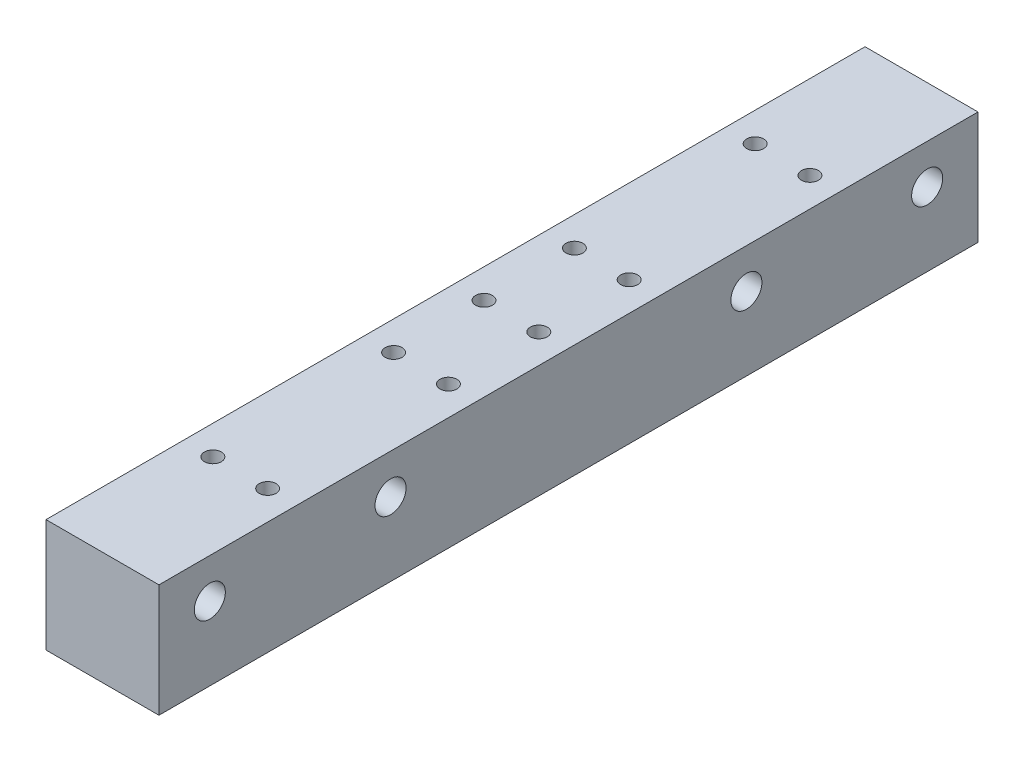
SolidWorks part; units mm, degrees
ref_plane "前视基准面" through (0, 0, 0) normal (0, 0, 1) x (1, 0, 0)
ref_plane "上视基准面" through (0, 0, 0) normal (0, 1, 0) x (1, 0, 0)
ref_plane "右视基准面" through (0, 0, 0) normal (1, 0, 0) x (0, 0, -1)
other "Configuration Table"
sketch "草图1" plane through (0, 0, 0) normal (0, 0, 1) x (1, 0, 0)
  line L1 (-10, -10) -> (10, -10)
  line L2 (-10, -10) -> (-10, 10)
  line L3 (-10, 10) -> (10, 10)
  line L4 (10, -10) -> (10, 10)
  line L5 (-10, -10) -> (10, 10) construction
  line L6 (-10, 10) -> (10, -10) construction
  line L11 (-8, -8) -> (8, 8) construction
  line L12 (-8, 8) -> (8, -8) construction
  point P0 (0, 0)
  point P6 (0, 0)
  dimension "D1" = 20
  dimension "D2" = 20
extrude "凸台-拉伸1" add sketch "草图1" along normal blind 145
sketch "草图2" plane through (10, 0, 0) normal (1, 0, 0) x (0, 0, -1)
  line L0 (-145, -10) -> (-145, 10) construction
  line L1 (-145, 10) -> (0, 10) construction
  line L2 (-72.5, -10) -> (-72.5, 10) construction
  line L3 (-145, -10) -> (0, -10) construction
  circle A0 centre (-136, 3) radius 2.75
  circle A1 centre (-104, 3) radius 2.75
  circle A2 centre (-9, 3) radius 2.75
  circle A3 centre (-41, 3) radius 2.75
  dimension "D1" = 5.5
  dimension "D3" = 13
  dimension "D4" = 32
  dimension "D2" = 9
extrude "切除-拉伸1" cut sketch "草图2" against normal up to surface (20 mm away) up to face at (-10, 0, 72.5)
sketch "草图3" plane through (0, -10, 0) normal (0, -1, 0) x (1, 0, 0)
  line L0 (0, 0) -> (0, 145) construction
  line L1 (-10, 145) -> (10, 145) construction
  circle A0 centre (0, 72.5) radius 1.5
  circle A1 centre (0, 88.5) radius 1.5
  circle A2 centre (0, 120.5) radius 1.5
  circle A3 centre (0, 56.5) radius 1.5
  circle A4 centre (0, 24.5) radius 1.5
  dimension "D1" = 3
  dimension "D2" = 16
  dimension "D3" = 16
  dimension "D4" = 32
  dimension "D5" = 32
extrude "切除-拉伸2" [suppressed] cut sketch "草图3" against normal up to surface (20 mm away)
sketch "草图4" plane through (0, 10, 0) normal (0, 1, 0) x (1, 0, 0)
  line L0 (0, 0) -> (0, -145) construction
  line L2 (10, -145) -> (-10, -145) construction
  circle A10 centre (-4.85, -24.607) radius 1.5
  circle A11 centre (-4.85, -56.607) radius 1.5
  circle A12 centre (-4.85, -72.607) radius 1.5
  circle A13 centre (-4.85, -88.607) radius 1.5
  circle A14 centre (-4.85, -120.607) radius 1.5
  circle A15 centre (4.85, -120.607) radius 1.5
  circle A16 centre (4.85, -88.607) radius 1.5
  circle A17 centre (4.85, -72.607) radius 1.5
  circle A18 centre (4.85, -56.607) radius 1.5
  circle A19 centre (4.85, -24.607) radius 1.5
  dimension "D1" = 3
extrude "切除-拉伸4" cut sketch "草图4" against normal up to surface (20 mm away) up to face at (0, -10, 72.5)
